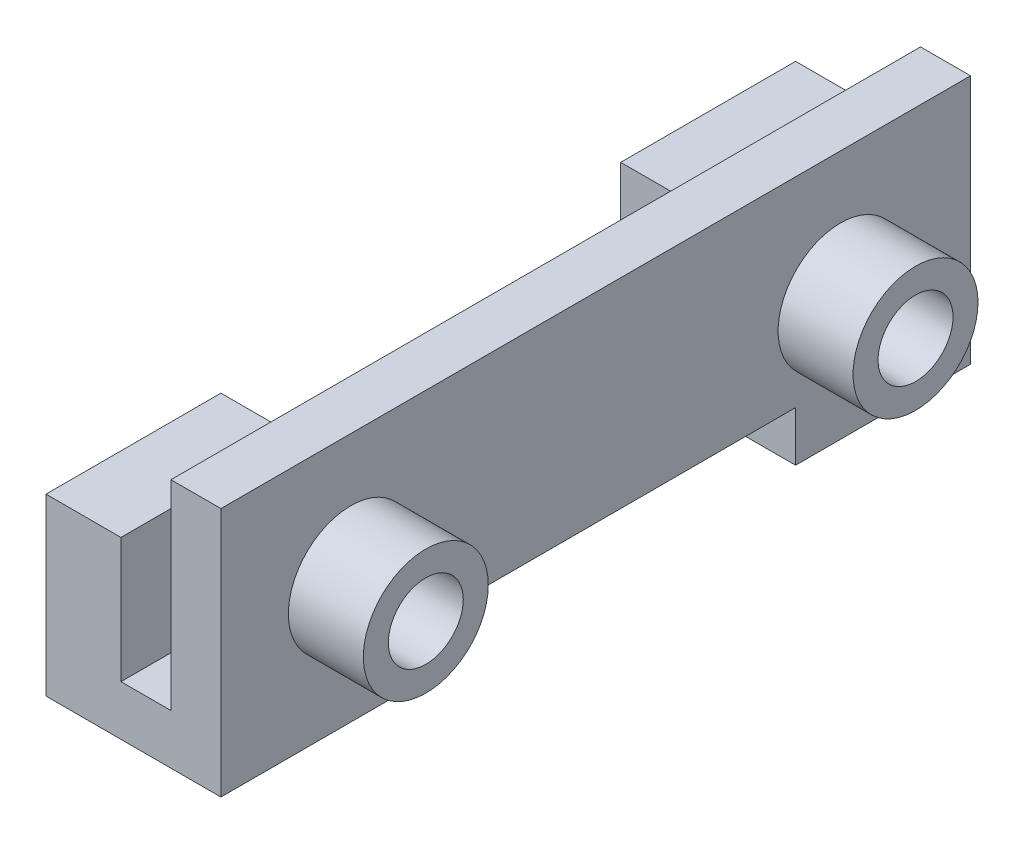
SolidWorks part; units mm, degrees
ref_plane "Front Plane" through (0, 0, 0) normal (0, 0, 1) x (1, 0, 0)
ref_plane "Top Plane" through (0, 0, 0) normal (0, 1, 0) x (1, 0, 0)
ref_plane "Right Plane" through (0, 0, 0) normal (1, 0, 0) x (0, 0, -1)
sketch "Esquisse1" plane through (0, 0, 0) normal (1, 0, 0) x (0, 0, -1)
  line L1 (-15, 5) -> (15, 5)
  line L2 (-15, 5) -> (-15, -5)
  line L3 (-15, -5) -> (15, -5)
  line L4 (15, 5) -> (15, -5)
  line L5 (-15, 5) -> (15, -5) construction
  line L6 (-15, -5) -> (15, 5) construction
  point P0 (0, 0)
extrude "Boss.-Extru.1" add sketch "Esquisse1" along normal blind 2
sketch "Esquisse2" plane through (2, 0, 0) normal (1, 0, 0) x (0, 0, -1)
  line L0 (-15, -5) -> (15, -5) construction
  circle A0 centre (-9.8, 0) radius 2.5
  circle A1 centre (9.8, 0) radius 2.5
  dimension "D1" = 5
  dimension "D2" = 9.8
  dimension "D3" = 9.8
extrude "Boss.-Extru.2" add sketch "Esquisse2" along normal blind 3 contours A1 | A0
sketch "Esquisse3" plane through (5, 0, 0) normal (1, 0, 0) x (0, 0, -1)
  circle A0 centre (-9.8, 0) radius 1.5
extrude "Enlèv. mat.-Extru.1" cut sketch "Esquisse3" against normal through all contours A0
sketch "Esquisse4" plane through (5, 0, 0) normal (1, 0, 0) x (0, 0, -1)
  circle A0 centre (9.8, 0) radius 1.5
extrude "Enlèv. mat.-Extru.2" cut sketch "Esquisse4" against normal through all
ref_plane "Plan1" through (0, 0, 0) normal (0, 0, 1) x (1, 0, 0)
sketch "Esquisse7" plane through (0, -5, 0) normal (0, -1, 0) x (1, 0, 0)
  line L0 (0, 0) -> (2, 0) construction
  line L1 (0, 15) -> (0, -15) construction
  line L2 (2, 15) -> (2, -15) construction
  line L4 (0, 8) -> (2, 8)
  line L5 (0, 8) -> (0, 0)
  line L6 (0, 0) -> (2, 0)
  line L7 (2, 8) -> (2, 0)
extrude "Enlèv. mat.-Extru.3" cut sketch "Esquisse7" against normal blind 2
mirror "Symétrie1" about plane through (0, 0, 0) normal (0, 0, 1) of "Enlèv. mat.-Extru.3"
sketch "Esquisse8" plane through (0, 0, 0) normal (-1, 0, 0) x (0, 0, 1)
  line L1 (-15, -5) -> (-8, -5)
  line L2 (-15, -5) -> (-15, -3)
  line L3 (-15, -3) -> (-8, -3)
  line L4 (-8, -5) -> (-8, -3)
extrude "Boss.-Extru.3" add sketch "Esquisse8" along normal blind 5
sketch "Esquisse12" plane through (0, -3, 0) normal (0, 1, 0) x (1, 0, 0)
  line L0 (-5, 8) -> (0, 8) construction
  line L1 (-5, 15) -> (-2, 15)
  line L2 (-5, 15) -> (-5, 8)
  line L3 (-5, 8) -> (-2, 8)
  line L4 (-2, 15) -> (-2, 8)
extrude "Boss.-Extru.4" add sketch "Esquisse12" along normal blind 5
mirror "Symétrie2" about plane through (0, 0, 0) normal (0, 0, 1) of "Boss.-Extru.4", "Boss.-Extru.3"
